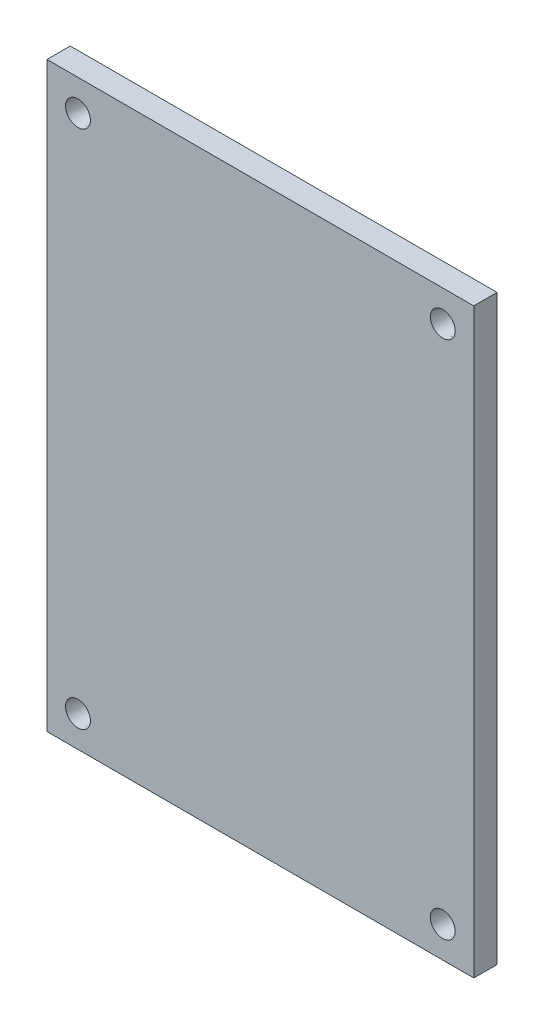
SolidWorks part; units mm, degrees
ref_plane "Front Plane" through (0, 0, 0) normal (1, 0, 0) x (0, 1, 0)
ref_plane "Top Plane" through (0, 0, 0) normal (0, 0, 1) x (0, 1, 0)
ref_plane "Right Plane" through (0, 0, 0) normal (0, 1, 0) x (-1, 0, 0)
sketch "Sketch1" plane through (0, 0, 0) normal (0, 0, 1) x (0, 1, 0)
  line L1 (37.5, -27.5) -> (-37.5, -27.5)
  line L2 (37.5, -27.5) -> (37.5, 27.5)
  line L3 (37.5, 27.5) -> (-37.5, 27.5)
  line L4 (-37.5, -27.5) -> (-37.5, 27.5)
  line L5 (37.5, -27.5) -> (-37.5, 27.5) construction
  line L6 (37.5, 27.5) -> (-37.5, -27.5) construction
  point P0 (0, 0)
  dimension "D1" = 75
  dimension "D2" = 55
extrude "Boss-Extrude1" add sketch "Sketch1" along normal blind 3
sketch "Sketch2" plane through (0, 0, 3) normal (0, 0, 1) x (1, 0, 0)
  line L1 (23.5, -33.5) -> (-23.5, -33.5)
  line L2 (23.5, -33.5) -> (23.5, 33.5)
  line L3 (23.5, 33.5) -> (-23.5, 33.5)
  line L4 (-23.5, -33.5) -> (-23.5, 33.5)
  line L5 (23.5, -33.5) -> (-23.5, 33.5) construction
  line L6 (23.5, 33.5) -> (-23.5, -33.5) construction
  circle A0 centre (-23.5, 33.5) radius 1.6
  circle A1 centre (23.5, 33.5) radius 1.6
  circle A2 centre (-23.5, -33.5) radius 1.6
  circle A3 centre (23.5, -33.5) radius 1.6
  point P0 (0, 0)
  dimension "D1" = 3.2
  dimension "D2" = 47
  dimension "D3" = 67
extrude "Cut-Extrude1" cut sketch "Sketch2" against normal through all draft 5 contours A3 | A2 | A0 | A1
